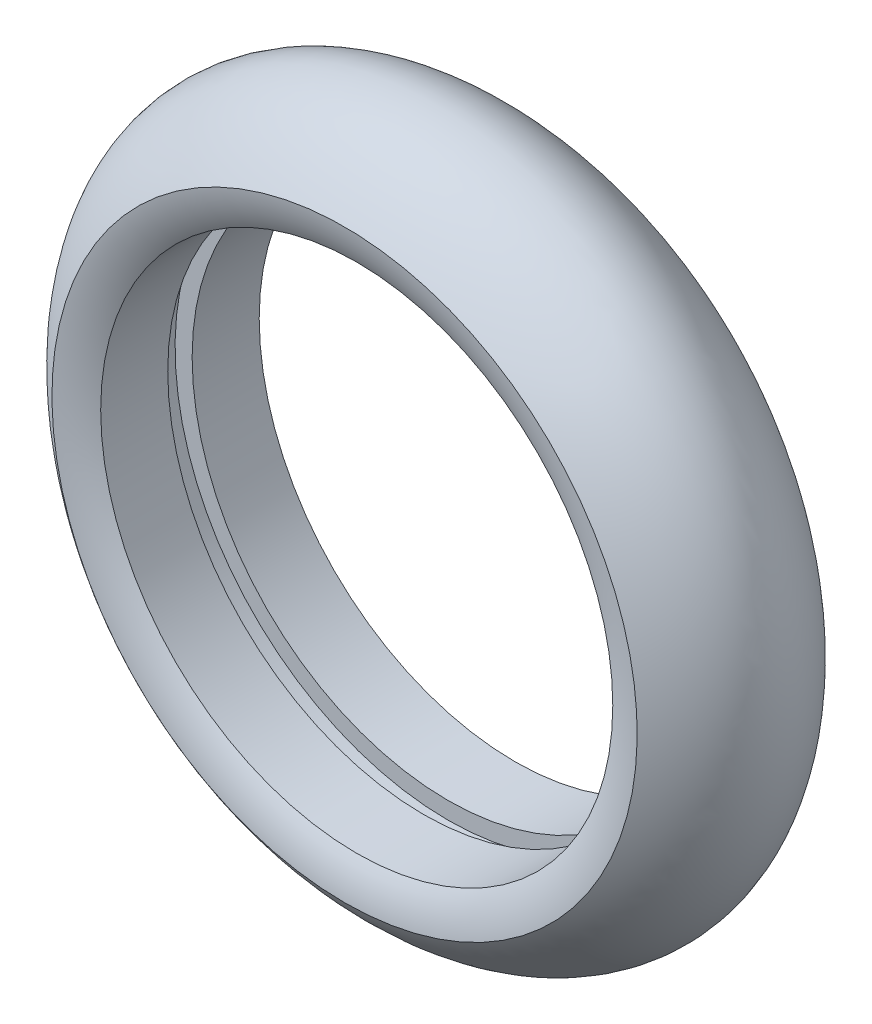
SolidWorks part; units mm, degrees
ref_plane "Front Plane" through (0, 0, 0) normal (0, 0, 1) x (1, 0, 0)
ref_plane "Top Plane" through (0, 0, 0) normal (0, 1, 0) x (1, 0, 0)
ref_plane "Right Plane" through (0, 0, 0) normal (1, 0, 0) x (0, 0, -1)
sketch "Sketch1" plane through (0, 0, 0) normal (1, 0, 0) x (0, 0, -1)
  line L0 (0, 21) -> (0, 0) construction
  line L5 (-7.5, 29) -> (7.5, 29)
  line L6 (-7.5, 29) -> (-7.5, 21)
  line L7 (-7.5, 21) -> (7.5, 21)
  line L8 (7.5, 29) -> (7.5, 21)
  line L9 (-7.5, 24) -> (-6.5, 24)
  line L10 (-6.5, 24) -> (-6.5, 21)
  line L11 (6.5, 21) -> (6.5, 24)
  line L12 (6.5, 24) -> (7.5, 24)
  line L13 (-13.3609, 0) -> (13.3609, 0)
  arc A0 (-6.5, 21) -> (-7.5, 24) centre (0, 24.8333) cw
  arc A1 (6.5, 21) -> (7.5, 24) centre (0, 24.8333) ccw
  ellipse E0 centre (0, 0) end of major axis (0, 29) minor radius 13.3609
  dimension "D1" = 15
  dimension "D2" = 29
  dimension "D3" = 21
  dimension "D4" = 1
  dimension "D5" = 3
sketch "Sketch3" plane through (0, 0, 0) normal (1, 0, 0) x (0, 0, -1)
  line L0 (-6.5, 21) -> (-1, 21)
  line L1 (-1, 21) -> (-1, 22.4)
  line L2 (-1, 22.4) -> (1, 22.4)
  line L3 (1, 22.4) -> (1, 21)
  line L4 (1, 21) -> (6.5, 21)
  arc A0 (-6.5, 21) -> (-7.5, 24) centre (0, 24.8333) cw
  arc A1 (7.5, 24) -> (6.5, 21) centre (0, 24.8333) cw
  ellipse E0 centre (0, 0) end of major axis (0, 29) minor radius 13.3609 (-7.5, 24) -> (7.5, 24) cw
  point P6 (0, 22.4)
  dimension "D1" = 1.4
  dimension "D2" = 2
revolve "Revolve1" add sketch "Sketch3" angle 360 about L13
